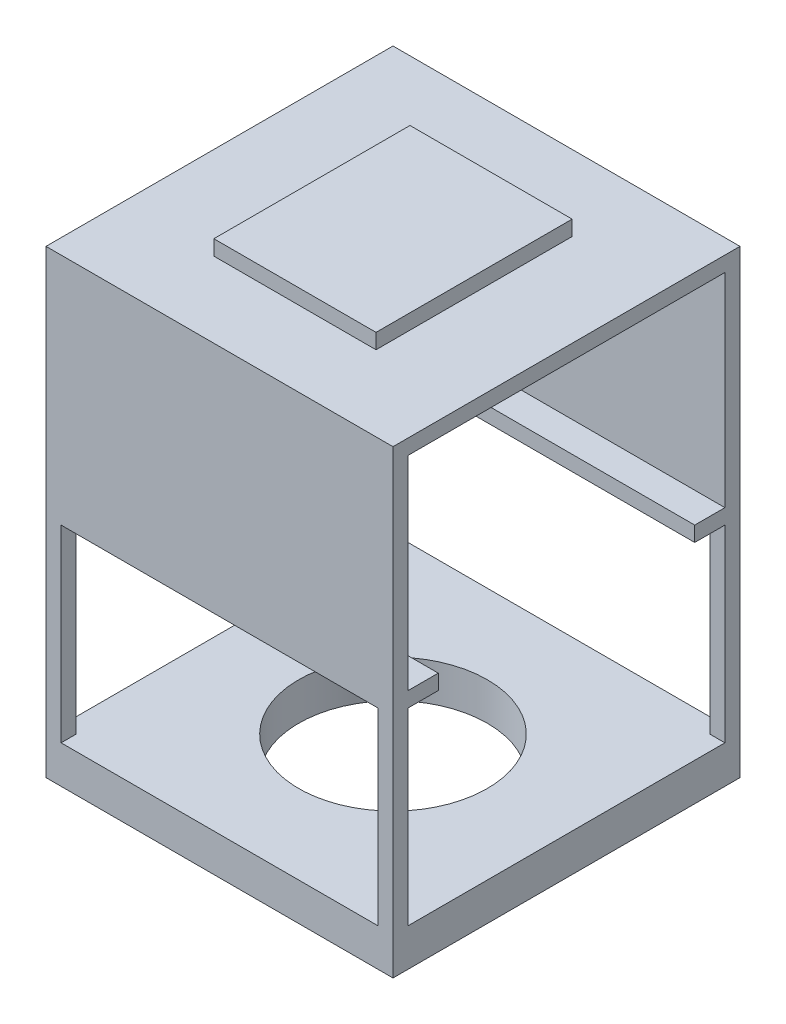
SolidWorks part; units mm, degrees
ref_plane "Alzado" through (0, 0, 0) normal (0, 0, 1) x (1, 0, 0)
ref_plane "Planta" through (0, 0, 0) normal (0, 1, 0) x (1, 0, 0)
ref_plane "Vista lateral" through (0, 0, 0) normal (1, 0, 0) x (0, 0, -1)
sketch "Croquis1" plane through (0, 0, 0) normal (0, 1, 0) x (1, 0, 0)
  line L1 (-10.75, -13) -> (10.75, -13)
  line L2 (-10.75, -13) -> (-10.75, 13)
  line L3 (-10.75, 13) -> (10.75, 13)
  line L4 (10.75, -13) -> (10.75, 13)
  line L5 (-10.75, -13) -> (10.75, 13) construction
  line L6 (-10.75, 13) -> (10.75, -13) construction
  point P0 (0, 0)
  dimension "D1" = 21.5
  dimension "D2" = 26
extrude "Saliente-Extruir1" add sketch "Croquis1" along normal blind 2
sketch "Croquis2" plane through (0, 0, 0) normal (0, -1, 0) x (1, 0, 0)
  line L1 (-23, -23) -> (23, -23)
  line L2 (-23, -23) -> (-23, 23)
  line L3 (-23, 23) -> (23, 23)
  line L4 (23, -23) -> (23, 23)
  line L5 (-23, -23) -> (23, 23) construction
  line L6 (-23, 23) -> (23, -23) construction
  point P0 (0, 0)
  dimension "D1" = 46
  dimension "D2" = 46
extrude "Saliente-Extruir2" add sketch "Croquis2" along normal blind 2
sketch "Croquis3" plane through (0, -2, 0) normal (0, -1, 0) x (1, 0, 0)
  line L0 (-23, 23) -> (-23, -23)
  line L1 (-23, -23) -> (23, -23)
  line L2 (23, -23) -> (23, 23)
  line L3 (23, 23) -> (-23, 23)
  line L4 (-21, 21) -> (-21, -21)
  line L5 (-21, -21) -> (21, -21)
  line L6 (21, -21) -> (21, 21)
  line L7 (-21, 21) -> (21, 21)
  dimension "D1" = 2
  dimension "D2" = 2
  dimension "D3" = 2
  dimension "D4" = 2
extrude "Saliente-Extruir3" add sketch "Croquis3" along normal blind 29
sketch "Croquis4" plane through (23, 0, 0) normal (1, 0, 0) x (0, 0, -1)
  line L0 (-21, -31) -> (-21, -2)
  line L1 (23, -31) -> (-23, -31) construction
  line L2 (-21, -2) -> (21, -2)
  line L3 (21, -2) -> (21, -31)
  line L4 (21, -31) -> (-21, -31)
  line L5 (-23, -31) -> (-23, 0) construction
  line L6 (23, 0) -> (-23, 0) construction
  line L7 (23, -31) -> (23, 0) construction
  dimension "D1" = 2
  dimension "D2" = 2
  dimension "D3" = 2
extrude "Cortar-Extruir1" cut sketch "Croquis4" against normal blind 29
sketch "Croquis5" plane through (0, -31, 0) normal (0, -1, 0) x (1, 0, 0)
  line L0 (23, 17) -> (-17, 17)
  line L1 (-23, 23) -> (23, 23)
  line L2 (-23, 23) -> (-23, -23)
  line L3 (-23, -23) -> (23, -23)
  line L4 (23, 17) -> (23, 23)
  line L5 (-17, 17) -> (-17, -17)
  line L6 (-17, -17) -> (23, -17)
  line L7 (23, -17) -> (23, -23)
  dimension "D1" = 6
  dimension "D2" = 6
  dimension "D3" = 6
extrude "Saliente-Extruir4" add sketch "Croquis5" against normal blind 2
sketch "Croquis6" plane through (0, -31, 0) normal (0, -1, 0) x (1, 0, 0)
  line L1 (-23, 23) -> (-21, 23)
  line L2 (-23, 23) -> (-23, 21)
  line L3 (-23, 21) -> (-21, 21)
  line L4 (-21, 23) -> (-21, 21)
  line L5 (23, 23) -> (21, 23)
  line L6 (23, 23) -> (23, 21)
  line L7 (23, 21) -> (21, 21)
  line L8 (21, 23) -> (21, 21)
  line L9 (-23, -23) -> (-21, -23)
  line L10 (-23, -23) -> (-23, -21)
  line L11 (-23, -21) -> (-21, -21)
  line L12 (-21, -23) -> (-21, -21)
  line L13 (23, -23) -> (21, -23)
  line L14 (23, -23) -> (23, -21)
  line L15 (23, -21) -> (21, -21)
  line L16 (21, -23) -> (21, -21)
  dimension "D1" = 2
extrude "Saliente-Extruir5" add sketch "Croquis6" along normal blind 30
sketch "Croquis7" plane through (0, -61, 0) normal (0, -1, 0) x (1, 0, 0)
  line L1 (-23, 23) -> (23, 23)
  line L2 (-23, 23) -> (-23, -23)
  line L3 (-23, -23) -> (23, -23)
  line L4 (23, 23) -> (23, -23)
extrude "Saliente-Extruir6" add sketch "Croquis7" against normal blind 5
sketch "Croquis8" plane through (0, -61, 0) normal (0, -1, 0) x (1, 0, 0)
  circle A0 centre (0, 0) radius 12.5
  dimension "D1" = 25
extrude "Cortar-Extruir2" cut sketch "Croquis8" against normal blind 30
